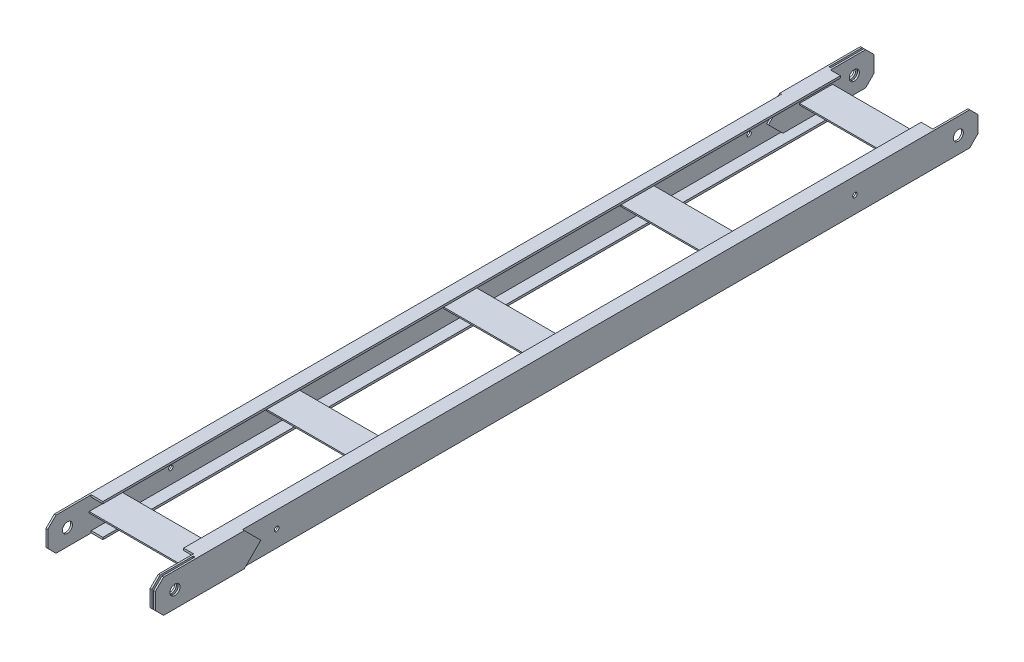
SolidWorks part; units mm, degrees
ref_plane "前视基准面" through (0, 0, 0) normal (0, 0, 1) x (1, 0, 0)
ref_plane "上视基准面" through (0, 0, 0) normal (0, 1, 0) x (1, 0, 0)
ref_plane "右视基准面" through (0, 0, 0) normal (1, 0, 0) x (0, 0, -1)
sketch "草图2" plane through (0, 0, 0) normal (0, 0, 1) x (1, 0, 0)
  line L0 (0, 0) -> (0, 160)
  line L1 (0, 160) -> (65, 160)
  line L2 (65, 160) -> (65, 150)
  line L3 (65, 150) -> (8.5, 150)
  line L4 (8.5, 150) -> (8.5, 10)
  line L5 (8.5, 10) -> (65, 10)
  line L6 (65, 10) -> (65, 0)
  line L7 (65, 0) -> (0, 0)
  line L8 (455, 160) -> (520, 160)
  line L9 (520, 160) -> (520, 0)
  line L10 (520, 0) -> (455, 0)
  line L11 (455, 0) -> (455, 10)
  line L12 (455, 10) -> (511.5, 10)
  line L13 (511.5, 10) -> (511.5, 150)
  line L14 (511.5, 150) -> (455, 150)
  line L15 (455, 150) -> (455, 160)
  dimension "D1" = 160
  dimension "D2" = 10
  dimension "D3" = 8.5
  dimension "D4" = 65
  dimension "D5" = 520
extrude "拉伸1" add sketch "草图2" along normal blind 3985
sketch "草图5" plane through (0, 0, 0) normal (-1, 0, 0) x (0, 0, 1)
  line L0 (200, 95) -> (360, 95)
  line L1 (360, 95) -> (360, 88.5)
  line L2 (283.25, 88.5) -> (360, 88.5)
  line L3 (283.25, 88.5) -> (283.25, 48.5)
  line L4 (283.25, 48.5) -> (276.75, 48.5)
  line L5 (276.75, 48.5) -> (276.75, 88.5)
  line L6 (276.75, 88.5) -> (200, 88.5)
  line L7 (200, 88.5) -> (200, 95)
  line L8 (0, 160) -> (0, 0) construction
  point P10 (0, 80)
  dimension "D1" = 160
  dimension "D2" = 6.5
  dimension "D3" = 6.5
  dimension "D4" = 40
  dimension "D5" = 200
  dimension "D6" = 15
extrude "拉伸3" add sketch "草图5" against normal blind 520
sketch "草图6" plane through (0, 160, 0) normal (0, 1, 0) x (1, 0, 0)
  line L0 (520, 0) -> (455, 0) construction
  line L1 (511.5, 0) -> (8.5, 0)
  line L2 (511.5, 0) -> (511.5, -200)
  line L3 (511.5, -200) -> (8.5, -200)
  line L4 (8.5, 0) -> (8.5, -200)
  line L5 (65, -3985) -> (0, -3985) construction
  line L6 (511.5, -3785) -> (8.5, -3785)
  line L7 (511.5, -3785) -> (511.5, -3985)
  line L8 (511.5, -3985) -> (8.5, -3985)
  line L9 (8.5, -3785) -> (8.5, -3985)
  line L10 (520, -3985) -> (520, 0) construction
  line L11 (0, -3985) -> (0, 0) construction
  dimension "D1" = 8.5
  dimension "D2" = 8.5
  dimension "D3" = 200
  dimension "D4" = 200
  dimension "D5" = 8.5
  dimension "D6" = 8.5
extrude "拉伸4" cut sketch "草图6" against normal through all
pattern_linear "阵列(线性)1" count 5 spacing 856.25 along (0, 0, 1) of "拉伸3"
sketch "草图19" plane through (520, 0, 0) normal (1, 0, 0) x (0, 0, -1)
  line L0 (-3985, 0) -> (0, 0) construction
  line L1 (-3985, 160) -> (-3555, 160)
  line L2 (-3985, 160) -> (-3985, 0)
  line L3 (-3985, 0) -> (-3555, 0)
  line L4 (-3555, 160) -> (-3475, 80)
  line L5 (-3475, 80) -> (-3555, 0)
  dimension "D1" = 430
extrude "拉伸11" add sketch "草图19" along normal blind 8.5
pattern_linear "阵列(线性)2" count 2 spacing 17 along (-1, 0, 0) of "拉伸11"
sketch "草图22" plane through (0, 160, 0) normal (0, 1, 0) x (1, 0, 0)
  line L0 (528.5, -3985) -> (503, -3985) construction
  line L1 (511.5, -3785) -> (520, -3785)
  line L2 (511.5, -3785) -> (511.5, -3985)
  line L3 (511.5, -3985) -> (520, -3985)
  line L4 (520, -3785) -> (520, -3985)
  line L5 (528.5, -3555) -> (528.5, -3985) construction
  line L6 (503, -3785) -> (503, -3985) construction
  line L7 (503, -3785) -> (455, -3785) construction
  dimension "D1" = 8.5
  dimension "D2" = 8.5
extrude "拉伸12" cut sketch "草图22" against normal through all
sketch "草图23" plane through (0, 0, 0) normal (-1, 0, 0) x (0, 0, 1)
  line L0 (0, 160) -> (0, 0) construction
  line L2 (3985, 0) -> (0, 0) construction
  line L3 (3985, 160) -> (3985, 0) construction
  line L4 (3985, 160) -> (0, 160) construction
  circle A0 centre (95, 80) radius 24.25
  circle A1 centre (3890, 80) radius 24.25
  dimension "D3" = 48.5
  dimension "D4" = 48.5
  dimension "D1" = 95
  dimension "D2" = 80
  dimension "D5" = 95
  dimension "D6" = 80
extrude "拉伸13" cut sketch "草图23" against normal through all
sketch "草图26" plane through (0, 0, 0) normal (-1, 0, 0) x (0, 0, 1)
  line L0 (0, 160) -> (0, 0)
  line L1 (0, 160) -> (430, 160)
  line L2 (430, 160) -> (510, 80)
  line L3 (510, 80) -> (430, 0)
  line L4 (0, 0) -> (430, 0)
  dimension "D1" = 430
extrude "拉伸14" add sketch "草图26" along normal blind 8.5
pattern_linear "阵列(线性)3" count 2 spacing 17 along (1, 0, 0) of "拉伸14"
sketch "草图27" plane through (0, 160, 0) normal (0, 1, 0) x (1, 0, 0)
  line L0 (17, 0) -> (-8.5, 0) construction
  line L1 (0, 0) -> (8.5, 0)
  line L2 (0, 0) -> (0, -200)
  line L3 (0, -200) -> (8.5, -200)
  line L4 (8.5, 0) -> (8.5, -200)
  line L5 (-8.5, -430) -> (-8.5, 0) construction
  line L6 (17, -200) -> (17, 0) construction
  line L7 (17, -200) -> (65, -200) construction
  dimension "D1" = 8.5
  dimension "D2" = 8.5
extrude "拉伸15" cut sketch "草图27" against normal through all
sketch "草图28" plane through (-8.5, 0, 0) normal (-1, 0, 0) x (0, 0, 1)
  line L0 (0, 160) -> (0, 0) construction
  line L1 (430, 160) -> (0, 160) construction
  circle A0 centre (95, 80) radius 24.25
  dimension "D1" = 48.5
  dimension "D2" = 95
  dimension "D3" = 80
extrude "拉伸16" cut sketch "草图28" against normal through all
sketch "草图29" plane through (0, 0, 3785) normal (0, 0, 1) x (1, 0, 0)
  line L1 (8.5, 160) -> (503, 160)
  line L2 (8.5, 160) -> (8.5, 150)
  line L3 (8.5, 150) -> (503, 150)
  line L4 (503, 160) -> (503, 150)
  line L5 (503, 0) -> (8.5, 0)
  line L6 (503, 0) -> (503, 10)
  line L7 (503, 10) -> (8.5, 10)
  line L8 (8.5, 0) -> (8.5, 10)
extrude "拉伸17" cut sketch "草图29" against normal blind 10
sketch "草图30" plane through (0, 0, 200) normal (0, 0, -1) x (-1, 0, 0)
  line L1 (-17, 160) -> (-511.5, 160)
  line L2 (-17, 160) -> (-17, 150)
  line L3 (-17, 150) -> (-511.5, 150)
  line L4 (-511.5, 160) -> (-511.5, 150)
  line L5 (-511.5, 10) -> (-17, 10)
  line L6 (-511.5, 10) -> (-511.5, 0)
  line L7 (-511.5, 0) -> (-17, 0)
  line L8 (-17, 10) -> (-17, 0)
extrude "拉伸18" cut sketch "草图30" against normal blind 10
sketch "草图31" plane through (520, 0, 0) normal (1, 0, 0) x (0, 0, -1)
  line L0 (-95, 80) -> (-3890, 80) construction
  circle A0 centre (-595, 80) radius 11
  circle A1 centre (-3390, 80) radius 11
  dimension "D1" = 22
  dimension "D2" = 22
  dimension "D3" = 500
  dimension "D4" = 500
extrude "拉伸19" cut sketch "草图31" against normal through all
chamfer "倒角1" distance 40 angle 45 14 edges at (-4.25, 0, 0) (507.25, 0, 3985) (4.25, 160, 3985) (4.25, 0, 3985) (507.25, 160, 3985) (524.25, 0, 3985) (-4.25, 160, 0) (12.75, 0, 0) (515.75, 160, 0) (524.25, 160, 3985) (515.75, 0, 0) (12.75, 160, 0)
